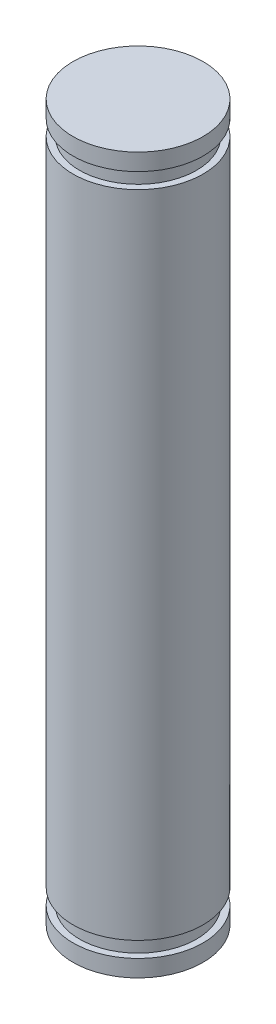
SolidWorks part; units mm, degrees
ref_plane "前视基准面" through (0, 0, 0) normal (0, 0, 1) x (1, 0, 0)
ref_plane "上视基准面" through (0, 0, 0) normal (0, 1, 0) x (1, 0, 0)
ref_plane "右视基准面" through (0, 0, 0) normal (1, 0, 0) x (0, 0, -1)
sketch "草图1" plane through (0, 0, 0) normal (0, 0, 1) x (1, 0, 0)
  line L12 (-6.9556, 21.1149) -> (-11.9556, 21.1149)
  line L13 (-11.9556, 21.1149) -> (-11.9556, 76.1149) construction
  line L14 (-6.9556, 21.1149) -> (-6.9556, 22.4149)
  line L15 (-6.9556, 22.4149) -> (-7.4556, 22.4149)
  line L16 (-7.4556, 22.4149) -> (-7.4556, 23.6149)
  line L17 (-7.4556, 23.6149) -> (-6.9556, 23.6149)
  line L18 (-6.9556, 23.6149) -> (-6.9556, 73.6149)
  line L19 (-6.9556, 73.6149) -> (-7.4556, 73.6149)
  line L20 (-7.4556, 73.6149) -> (-7.4556, 74.8149)
  line L21 (-7.4556, 74.8149) -> (-6.9556, 74.8149)
  line L22 (-6.9556, 74.8149) -> (-6.9556, 76.1149)
  line L23 (-6.9556, 76.1149) -> (-11.9556, 76.1149)
  line L24 (-11.9556, 21.1149) -> (-11.9556, 76.1149)
  dimension "D1" = 55
  dimension "D2" = 50
  dimension "D3" = 5
  dimension "D4" = 1.2
  dimension "D5" = 1.2
  dimension "D6" = 0.5
revolve "旋转1" add sketch "草图1" angle 360 about L13
